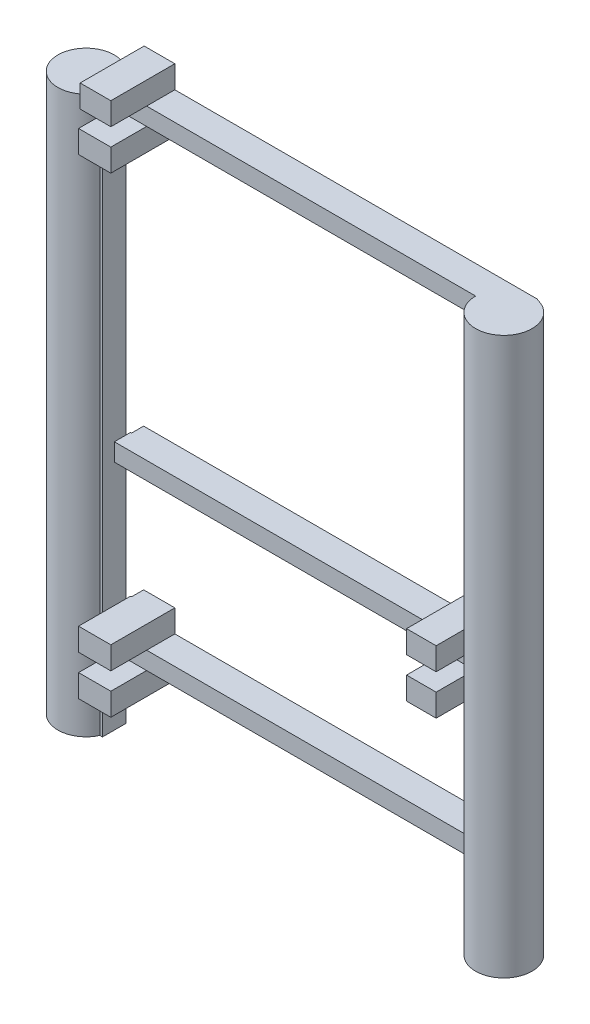
SolidWorks part; units mm, degrees
ref_plane "Front Plane" through (0, 0, 0) normal (0, 0, 1) x (1, 0, 0)
ref_plane "Top Plane" through (0, 0, 0) normal (0, 1, 0) x (1, 0, 0)
ref_plane "Right Plane" through (0, 0, 0) normal (1, 0, 0) x (0, 0, -1)
sketch "Sketch2" plane through (0, 0, 0) normal (0, 1, 0) x (1, 0, 0)
  line L0 (2.5, 0) -> (37, 0)
  circle A0 centre (0, 0) radius 2.5
  circle A1 centre (37, 0) radius 2.5
  dimension "D1" = 5
  dimension "D3" = 5
  dimension "D2" = 34.5
extrude "Boss-Extrude1" add sketch "Sketch2" along normal blind 49.3 contours A0 | A1
sketch "Sketch3" plane through (0, 0, 0) normal (0, 1, 0) x (1, 0, 0)
  line L0 (2.4996, -0.0454) -> (2.5, 0)
  line L1 (2.5, 0) -> (2.5, 2.5)
  line L2 (2.5, 2.5) -> (2.5, -2.5)
  line L3 (2.5, -2.5) -> (2.5, 0)
  line L4 (2.5, 2.5) -> (2.2678, 2.5)
  line L5 (2.2678, 2.5) -> (2.2678, -2.5)
  line L6 (2.2678, -2.5) -> (2.5, -2.5)
  circle A0 centre (0, 0) radius 2.5 construction
extrude "Boss-Extrude2" add sketch "Sketch3" along normal blind 49.3
ref_plane "Plane1" through (2.5, 0, 0) normal (1, 0, 0) x (0, 0, -1)
sketch "Sketch4" plane through (2.5, 0, 0) normal (1, 0, 0) x (0, 0, -1)
  line L0 (0, 0) -> (0, 6)
  line L1 (2.5, 6) -> (0, 6)
  line L2 (2.5, 0) -> (2.5, 49.3) construction
  line L3 (0, 6) -> (0, 7.56)
  line L4 (0, 7.56) -> (2.5, 7.56)
  line L5 (2.5, 7.56) -> (2.5, 6)
  line L6 (0, 7.56) -> (0, 20.56)
  line L7 (0, 20.56) -> (0, 22.12)
  line L8 (0, 22.12) -> (2.5, 22.12)
  line L9 (2.5, 22.12) -> (2.5, 20.56)
  line L10 (2.5, 20.56) -> (0, 20.56)
  line L11 (0, 22.12) -> (0, 47.74)
  line L12 (0, 47.74) -> (0, 49.3)
  line L13 (2.5, 49.3) -> (-2.5, 49.3) construction
  line L14 (0, 49.3) -> (2.5, 49.3)
  line L15 (2.5, 49.3) -> (2.5, 47.74)
  line L16 (2.5, 47.74) -> (0, 47.74)
  line M7 (2.5, 0) -> (2.5, 49.3)
  line M8 (2.5, 49.3) -> (-2.5, 49.3)
  dimension "D1" = 6
  dimension "D2" = 1.56
  dimension "D3" = 13
  dimension "D4" = 1.56
  dimension "D5" = 25.62
extrude "Boss-Extrude4" add sketch "Sketch4" along normal blind 35 contours L16 L12 M7 M8 | L10 L8 L7 M7 | L4 L3 L1 M7
ref_plane "Plane3" through (0, 7.56, 0) normal (0, 1, 0) x (1, 0, 0)
sketch "Sketch9" plane through (0, 7.56, 0) normal (0, 1, 0) x (1, 0, 0)
  line L0 (34.5, 0) -> (34.5, 2.5)
  line L2 (34.5, 0) -> (2.5, 0) construction
  line L5 (37, 2.5) -> (2.5, 2.5) construction
  line L6 (34.5, 2.5) -> (31.8842, 2.5)
  line L8 (31.8842, 2.5) -> (31.8842, -0.6446)
  line L12 (31.8842, -0.6446) -> (34.5, -0.6446)
  line L13 (34.5, -0.6446) -> (34.5, 0)
ref_plane "Plane4" through (0, 22.12, 0) normal (0, 1, 0) x (1, 0, 0)
sketch "Sketch10" plane through (0, 22.12, 0) normal (0, 1, 0) x (1, 0, 0)
  line L0 (31.776, 2.5) -> (31.776, -0.6535)
  line L1 (37.5, 2.5) -> (2.2678, 2.5) construction
  line L3 (31.8842, -0.6446) -> (34.5, -0.6446) construction
  line L4 (34.397, -0.6446) -> (34.397, 2.5)
  line L5 (34.5, 2.5) -> (31.8842, 2.5) construction
  line L6 (34.397, 2.5) -> (31.776, 2.5)
  line L7 (31.776, -0.6535) -> (31.776, -2.5296)
  line L9 (34.397, -2.5296) -> (34.397, -0.6446)
  line L10 (31.776, -2.5296) -> (31.776, -3.3942)
  line L11 (31.776, -3.3942) -> (34.397, -3.3942)
  line L12 (34.397, -3.3942) -> (34.397, -2.5296)
extrude "Boss-Extrude8" add sketch "Sketch10" along normal blind 2 contours L7 L10 L11 L12 L9 L4 L6 L0
ref_plane "Plane6" through (0, 20.56, 0) normal (0, -1, 0) x (-1, 0, 0)
ref_plane "Plane7" through (0, 21.34, 0) normal (0, 1, 0) x (1, 0, 0)
sketch "Sketch15" plane through (0, 20.56, 0) normal (0, -1, 0) x (1, 0, 0)
  line L0 (31.776, 3.3942) -> (31.776, -2.5)
  line L1 (37, -2.5) -> (2.5, -2.5) construction
  line L2 (31.776, 3.3942) -> (34.397, 3.3942)
  line L3 (34.397, 3.3942) -> (34.397, -2.5)
  line L4 (34.5, -2.5) -> (31.8842, -2.5) construction
  line L5 (34.397, -2.5) -> (31.776, -2.5)
extrude "Boss-Extrude10" add sketch "Sketch15" along normal blind 2
sketch "Sketch16" plane through (0, 7.56, 0) normal (0, 1, 0) x (1, 0, 0)
  line L0 (2.5, 2.5) -> (5.3586, 2.5)
  line L1 (37.5, 2.5) -> (2.2678, 2.5) construction
  line L2 (2.5, -2.75) -> (2.5, 2.75) construction
  line L3 (5.3586, 2.5) -> (5.3586, -3.1709)
  line L4 (5.3586, -3.1709) -> (2.5, -3.1709)
  line L5 (2.5, -3.1709) -> (2.5, 2.5)
extrude "Boss-Extrude11" add sketch "Sketch16" along normal blind 2 contours L4 L5 L0 L3
ref_plane "Plane9" through (0, 6, 0) normal (0, -1, 0) x (-1, 0, 0)
sketch "Sketch17" plane through (0, 6, 0) normal (0, -1, 0) x (-1, 0, 0)
  line L0 (-5.3586, -3.1709) -> (-5.3586, 2.5)
  line L1 (-37, 2.5) -> (-2.5, 2.5) construction
  line L2 (-5.3586, 2.5) -> (-2.5, 2.5)
  line L3 (-2.5, 2.75) -> (-2.5, -2.75) construction
  line L4 (-2.5, 2.5) -> (-2.5, -3.1709)
  line L5 (-2.5, -3.1709) -> (-5.3586, -3.1709)
extrude "Boss-Extrude12" add sketch "Sketch17" along normal blind 2 contours L4 L5 L0 L2
ref_plane "Plane10" through (0, 47.74, 0) normal (0, -1, 0) x (-1, 0, 0)
sketch "Sketch18" plane through (0, 47.74, 0) normal (0, -1, 0) x (-1, 0, 0)
  line L0 (-2.5, 2.5124) -> (-5.3586, 2.5)
  line L1 (-2.5, 2.2) -> (-2.5, -2.2) construction
  line L2 (-5.3586, 2.5) -> (-5.3586, -3.1709)
  line L3 (-5.3586, -3.1709) -> (-2.5, -3.1709)
  line L4 (-2.5, -3.1709) -> (-2.5, 2.5124)
extrude "Boss-Extrude13" add sketch "Sketch18" along normal blind 2 contours L4 L0 L2 L3
ref_plane "Plane12" through (0, 49.3, 0) normal (0, 1, 0) x (1, 0, 0)
sketch "Sketch21" plane through (0, 49.3, 0) normal (0, 1, 0) x (1, 0, 0)
  line L0 (5.3586, -3.1709) -> (5.3586, 2.5)
  line L1 (37.5, 2.5) -> (2.2678, 2.5) construction
  line L2 (5.3586, -3.1709) -> (2.6399, -3.1709)
  line L3 (5.3586, -3.1709) -> (2.5, -3.1709) construction
  line L4 (2.6399, -3.1709) -> (2.6399, 2.5)
  line L5 (2.6399, 2.5) -> (5.3586, 2.5)
extrude "Boss-Extrude16" add sketch "Sketch21" along normal blind 2
sketch "Sketch22" plane through (0, 0, 0) normal (0, 1, 0) x (1, 0, 0)
  line L0 (2.2678, 1.0522) -> (2.2678, 2.5)
  line L1 (2.2678, 2.5) -> (2.5, 2.5)
  line L2 (2.5, -2.2) -> (2.5, 2.2) construction
  line L3 (2.6399, 2.5) -> (2.2678, 2.5) construction
  line L5 (2.2678, 1.0522) -> (2.5, 1.0522)
  line L6 (2.2678, -2.5) -> (2.2678, -1.0522)
  line L7 (2.2678, -1.0522) -> (2.5, -1.0522)
  line L8 (2.5, -1.0522) -> (2.5, -2.5)
  line L9 (2.5, -3.1709) -> (2.5, -2.5) construction
  line L10 (2.5, -2.5) -> (2.2678, -2.5)
  line L13 (2.5, 2.5) -> (2.5934, 2.5)
  line L14 (2.5934, 2.5) -> (2.5934, 1.425)
  line L15 (2.5934, 1.425) -> (2.5, 1.425)
  line L16 (2.5, 1.425) -> (2.5, 1.0522)
extrude "Cut-Extrude3" cut sketch "Sketch22" along normal blind 49.4 contours L13 L14 L15 L16 L5 L0 L1 | L10 L6 L7 L8
